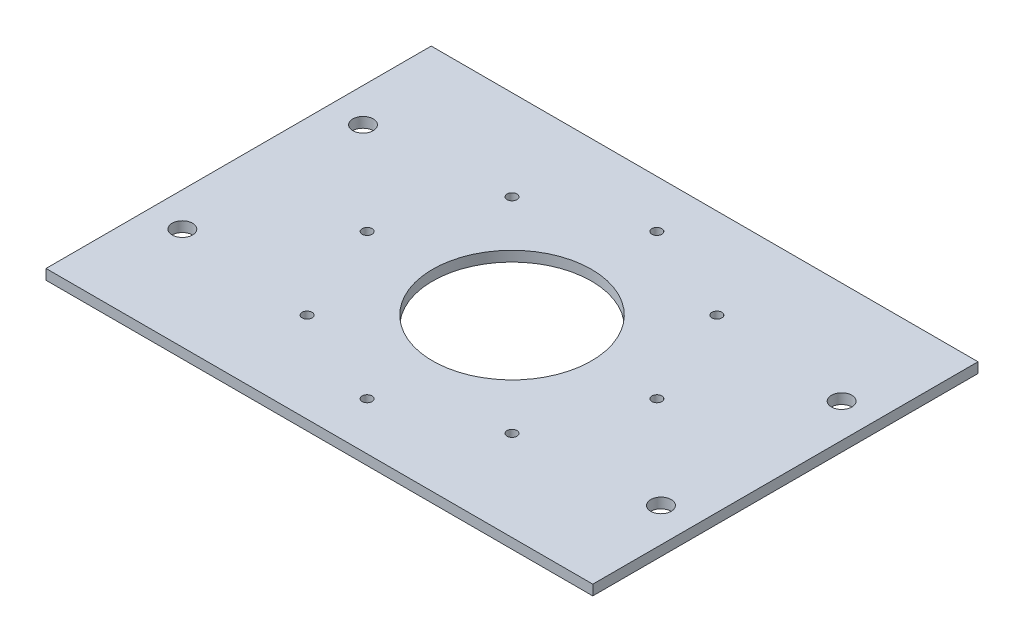
SolidWorks part; units mm, degrees
ref_plane "前视基准面" through (0, 0, 0) normal (0, 0, 1) x (1, 0, 0)
ref_plane "上视基准面" through (0, 0, 0) normal (0, 1, 0) x (1, 0, 0)
ref_plane "右视基准面" through (0, 0, 0) normal (1, 0, 0) x (0, 0, -1)
other "Configuration Table"
sketch "草图1" plane through (0, 0, 0) normal (0, 1, 0) x (1, 0, 0)
  line L1 (-80.2, 56.5) -> (80.2, 56.5)
  line L2 (-80.2, 56.5) -> (-80.2, -56.5)
  line L3 (-80.2, -56.5) -> (80.2, -56.5)
  line L4 (80.2, 56.5) -> (80.2, -56.5)
  line L5 (-80.2, 56.5) -> (80.2, -56.5) construction
  line L6 (-80.2, -56.5) -> (80.2, 56.5) construction
  point P0 (0, 0)
  dimension "D1" = 160.4
  dimension "D2" = 113
extrude "凸台-拉伸1" add sketch "草图1" along normal blind 3
sketch "草图2" plane through (0, 3, 0) normal (0, 1, 0) x (1, 0, 0)
  line L0 (-80.2, 0) -> (80.2, 0) construction
  line L1 (-80.2, 56.5) -> (-80.2, -56.5) construction
  line L2 (80.2, -56.5) -> (80.2, 56.5) construction
  line L3 (0, 56.5) -> (0, -56.5) construction
  line L4 (80.2, 56.5) -> (-80.2, 56.5) construction
  line L5 (-80.2, -56.5) -> (80.2, -56.5) construction
  circle A0 centre (0, 0) radius 42.5 construction
  circle A1 centre (0, -42.5) radius 1.45
  circle A2 centre (-30.052, -30.052) radius 1.45
  circle A3 centre (-42.5, 0) radius 1.45
  circle A4 centre (-30.052, 30.052) radius 1.45
  circle A5 centre (0, 42.5) radius 1.45
  circle A6 centre (30.052, 30.052) radius 1.45
  circle A7 centre (42.5, 0) radius 1.45
  circle A8 centre (30.052, -30.052) radius 1.45
  point P34 (0, 0)
  dimension "D1" = 85
  dimension "D2" = 2.9
  dimension "D3" = 8
extrude "切除-拉伸1" cut sketch "草图2" against normal blind 3
sketch "草图3" plane through (0, 0, 0) normal (0, -1, 0) x (1, 0, 0)
  circle A0 centre (0, 0) radius 23.2975
extrude "切除-拉伸2" cut sketch "草图3" against normal blind 3
sketch "草图4" plane through (0, 3, 0) normal (0, 1, 0) x (1, 0, 0)
  circle A0 centre (70.1985, -26.5) radius 3 construction
  circle A1 centre (70.1985, -26.5) radius 3
  circle A2 centre (-70.2, -26.5) radius 3 construction
  circle A3 centre (-70.2, -26.5) radius 3
  circle A4 centre (70.1985, 26.5) radius 3 construction
  circle A5 centre (70.1985, 26.5) radius 3
  circle A6 centre (-70.2, 26.5) radius 3 construction
  circle A7 centre (-70.2, 26.5) radius 3
extrude "切除-拉伸3" cut sketch "草图4" against normal blind 3
